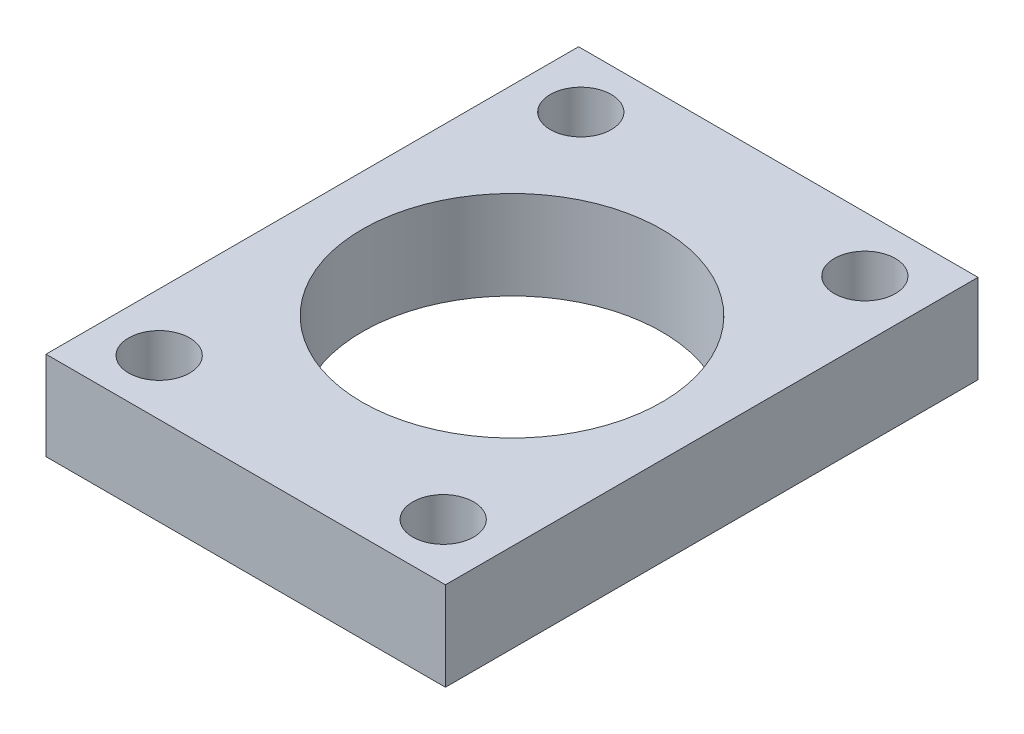
SolidWorks part; units mm, degrees
material "Plain Carbon Steel"
ref_plane "Front" through (0, 0, 0) normal (0, 0, 1) x (1, 0, 0)
ref_plane "Top" through (0, 0, 0) normal (0, 1, 0) x (1, 0, 0)
ref_plane "Right" through (0, 0, 0) normal (1, 0, 0) x (0, 0, -1)
sketch "Sketch1" plane through (0, 0, 0) normal (0, 1, 0) x (1, 0, 0)
  line L0 (-28.575, -38.1) -> (28.575, 38.1) construction
  line L1 (-28.575, 38.1) -> (28.575, 38.1)
  line L2 (-28.575, 38.1) -> (-28.575, -38.1)
  line L3 (-28.575, -38.1) -> (28.575, -38.1)
  line L4 (28.575, 38.1) -> (28.575, -38.1)
  dimension "D1" = 57.15
  dimension "D2" = 76.2
extrude "Extrude1" add sketch "Sketch1" along normal blind 12.7
hole_wizard "#10 Clearance Hole1" positions "Sketch3" profile "Sketch2" hole size "#10" standard "Ansi Inch"
sketch "Sketch3" plane through (0, 9.525, 0) normal (0, 1, 0) x (-1, 0, 0)
  point P0 (15.24, -15.24)
  point P1 (-15.24, -15.24)
  point P3 (-15.24, 15.24)
  point P5 (15.24, 15.24)
  dimension "D1" = 30.48
  dimension "D2" = 30.48
  dimension "D3" = 15.24
  dimension "D4" = 15.24
sketch "Sketch2" plane through (-15.24, 9.525, -15.24) normal (1, 0, 0) x (0, 0, 1)
  line L0 (0, 0) -> (0, 9.525)
  line L1 (0, 9.525) -> (2.8067, 9.525)
  line L2 (2.8067, 9.525) -> (2.8067, 0)
  line L5 (2.8067, 0) -> (0, 0)
  line L11 (0, -6.35) -> (0, 107.95) construction
  dimension "Thru Hole Dia." = 5.6134
  dimension "Thru Hole Depth" = 9.525
hole_wizard "3/4-16 Tapped Hole1" positions "Sketch5" profile "Sketch6" tap size "3/4-16" standard "Ansi Inch"
sketch "Sketch5" plane through (0, 9.525, 0) normal (0, 1, 0) x (-1, 0, 0)
  point P0 (0, 0)
sketch "Sketch6" plane through (0, 9.525, 0) normal (1, 0, 0) x (0, 0, 1)
  line L0 (0, 0) -> (0, 9.525)
  line L1 (0, 9.525) -> (8.7312, 9.525)
  line L2 (8.7312, 9.525) -> (8.7312, 0)
  line L5 (8.7312, 0) -> (0, 0)
  line L11 (0, -6.35) -> (0, 107.95) construction
  dimension "Thru Tap Drill Dia." = 17.4625
  dimension "Thru Tap Drill Depth" = 9.525
cosmetic thread "Hole Thread1" parameters "D2"=19.05
hole_wizard "1-12 Tapped Hole1" positions "Sketch8" profile "Sketch7" tap size "1-12" standard "Ansi Inch"
sketch "Sketch8" plane through (0, 9.525, 0) normal (0, 1, 0) x (-1, 0, 0)
  point P0 (0, 0)
sketch "Sketch7" plane through (0, 9.525, 0) normal (1, 0, 0) x (0, 0, 1)
  line L0 (0, 0) -> (0, 9.525)
  line L1 (0, 9.525) -> (11.7081, 9.525)
  line L2 (11.7081, 9.525) -> (11.7081, 0)
  line L5 (11.7081, 0) -> (0, 0)
  line L11 (0, -6.35) -> (0, 107.95) construction
  dimension "Thru Tap Drill Dia." = 23.4163
  dimension "Thru Tap Drill Depth" = 9.525
cosmetic thread "Hole Thread2" parameters "D2"=25.4
sketch "Sketch9" plane through (0, 12.7, 0) normal (0, 1, 0) x (-1, 0, 0)
  circle A0 centre (0, 0) radius 21.4312
  dimension "D1" = 42.8625
extrude "Cut-Extrude1" cut sketch "Sketch9" against normal through all
cosmetic thread "Cosmetic Thread1" parameters "D2"=44.45
hole_wizard "5/16 Clearance Hole1" positions "Sketch11" profile "Sketch10" hole size "5/16" standard "Ansi Inch" end condition through all
sketch "Sketch11" plane through (0, 12.7, 0) normal (0, 1, 0) x (-1, 0, 0)
  point P0 (20.32, -30.1625)
  point P1 (-20.32, -30.1625)
  point P3 (-20.32, 30.1625)
  point P5 (20.32, 30.1625)
  dimension "D1" = 40.64
  dimension "D2" = 60.325
  dimension "D3" = 30.1625
  dimension "D4" = 20.32
sketch "Sketch10" plane through (-20.32, 12.7, -30.1625) normal (1, 0, 0) x (0, 0, 1)
  line L0 (0, 0) -> (0, 12.7)
  line L1 (0, 12.7) -> (4.365, 12.7)
  line L2 (4.365, 12.7) -> (4.365, 0)
  line L5 (4.365, 0) -> (0, 0)
  line L11 (0, -6.35) -> (0, 107.95) construction
  dimension "Thru Hole Dia." = 8.73
  dimension "Thru Hole Depth" = 12.7
